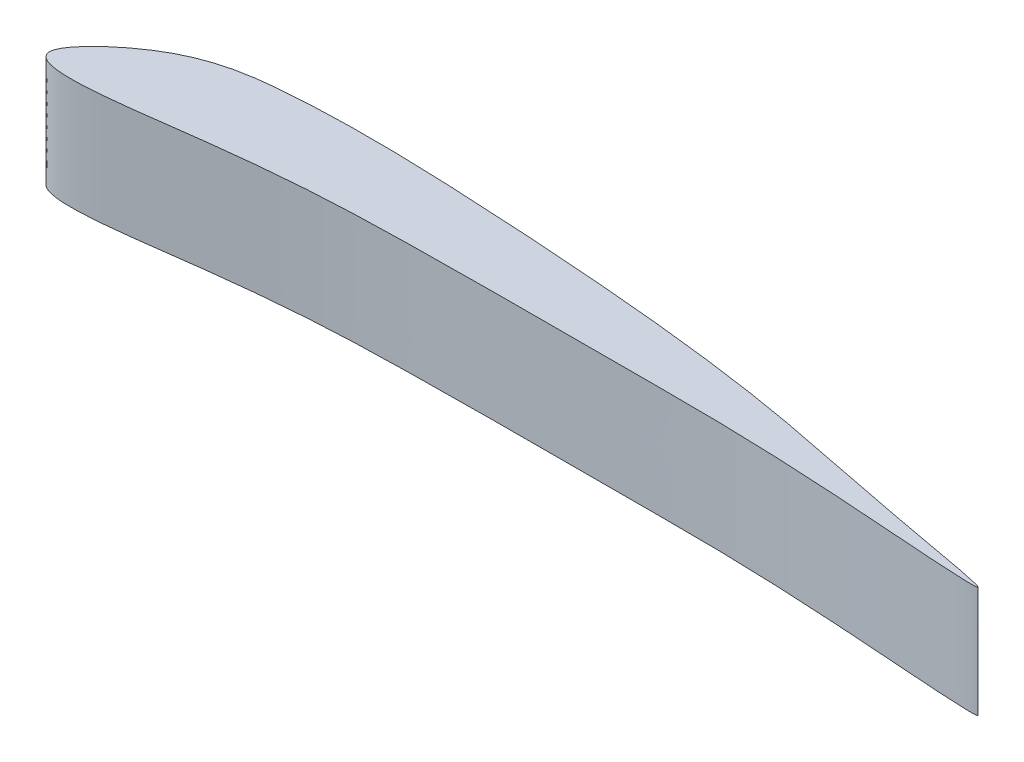
SolidWorks part; units mm, degrees
ref_plane "Front Plane" through (0, 0, 0) normal (0, 0, 1) x (1, 0, 0)
ref_plane "Top Plane" through (0, 0, 0) normal (0, 1, 0) x (1, 0, 0)
ref_plane "Right Plane" through (0, 0, 0) normal (1, 0, 0) x (0, 0, -1)
sketch "Sketch1" plane through (0, 0, 0) normal (0, 1, 0) x (1, 0, 0)
  line L0 (0, 0) -> (100, 0) construction
  spline S0 degree 3 poles (77.4606, 1.4848) (106.1204, -0.8886) (85.2626, 2.6993) (68.7392, 6.558) (41.8732, 8.7244) (19.4435, 9.4812) (6.8071, 7.6482) (-4.7674, -3.2642) (20.1107, 0.6079) (35.1173, 1.4413) (62.8658, 1.3523) (77.4606, 1.4848) (106.1204, -0.8886) (85.2626, 2.6993) knots -0.318125 -0.190926 -0.069158 0 0.040323 0.143748 0.307747 0.413694 0.470413 0.508331 0.578615 0.681875 0.809074 0.930842 1 1.040323 1.143748 1.307747 only from (100, 0) to (100, 0)
  point P3 (35.9924, 1.2816)
  point P5 (57.4331, 1.3837)
  point P8 (76.7442, 0.575)
  dimension "D1" = 100
  dimension "D2" = 91.9454
  dimension "D3" = 1.5871
  dimension "D4" = 71.2609
  dimension "D5" = 5.529
  dimension "D6" = 38.0241
  dimension "D7" = 8.7139
  dimension "D8" = 16.4542
  dimension "D9" = 8.8048
  dimension "D10" = 5.3785
  dimension "D11" = 5.5378
  dimension "D12" = 14.3028
  dimension "D13" = 0.4382
  dimension "D14" = 1.2351
  dimension "D15" = 1.3944
  dimension "D16" = 0.6773
  dimension "D17" = 35.259
  dimension "D18" = 61.1554
  dimension "D19" = 85.9363
extrude "Boss-Extrude1" add sketch "Sketch1" along normal blind 12
